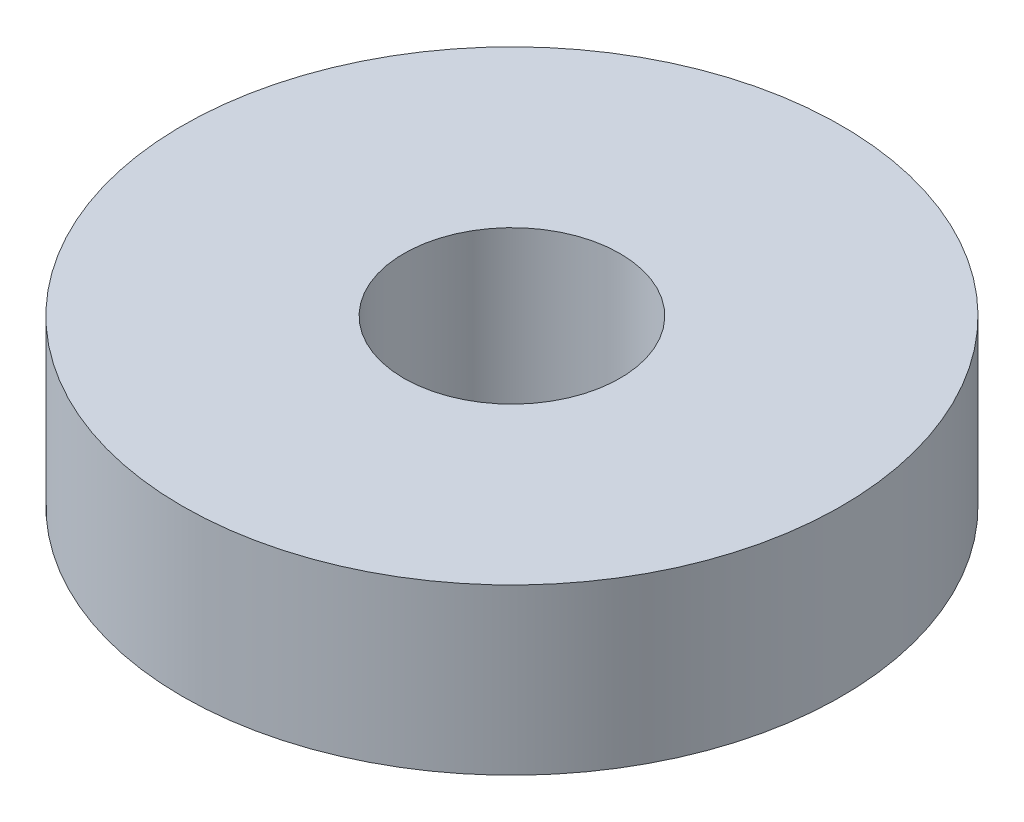
SolidWorks part; units mm, degrees
ref_plane "Front Plane" through (0, 0, 0) normal (0, 0, 1) x (1, 0, 0)
ref_plane "Top Plane" through (0, 0, 0) normal (0, 1, 0) x (1, 0, 0)
ref_plane "Right Plane" through (0, 0, 0) normal (1, 0, 0) x (0, 0, -1)
sketch "Sketch1" plane through (0, 0, 0) normal (0, 1, 0) x (1, 0, 0)
  circle A0 centre (0, 0) radius 2.0828
  circle A1 centre (0, 0) radius 6.35
  dimension "D1" = 4.1656
  dimension "D2" = 12.7
extrude "Boss-Extrude1" add sketch "Sketch1" along normal blind 3.175
